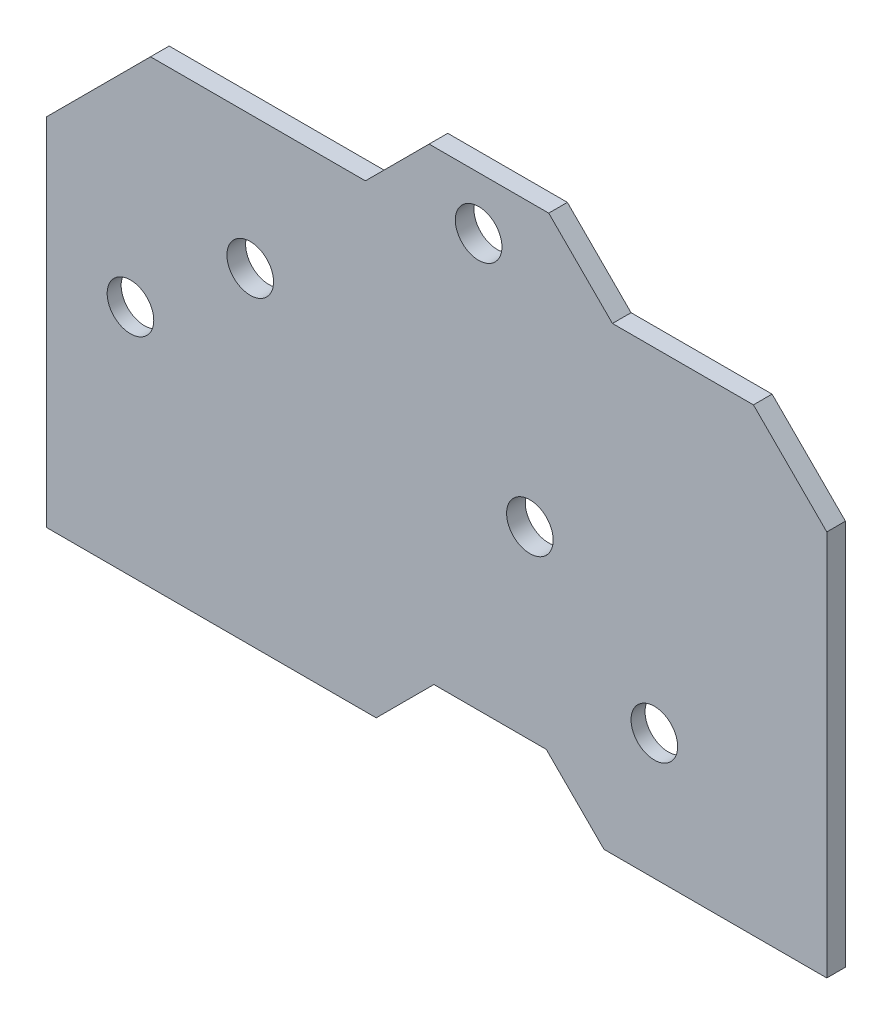
SolidWorks part; units mm, degrees
ref_plane "정면" through (0, 0, 0) normal (0, 0, 1) x (1, 0, 0)
ref_plane "윗면" through (0, 0, 0) normal (0, 1, 0) x (1, 0, 0)
ref_plane "우측면" through (0, 0, 0) normal (1, 0, 0) x (0, 0, -1)
sketch "스케치1" plane through (0, 0, 0) normal (0, 0, 1) x (1, 0, 0)
  line L0 (-7.6862, -28.1969) -> (-1.494, -22.0047)
  line L1 (-2.0116, 27.949) -> (10.8212, 27.949)
  line L2 (-43.0492, 9.9642) -> (-43.0492, -28.1969)
  line L3 (-43.0492, -28.1969) -> (-7.6862, -28.1969)
  line L4 (40.6497, 13.245) -> (40.6497, -28.1969)
  line L5 (-1.494, -22.0047) -> (10.5566, -22.0047)
  line L6 (10.5566, -22.0047) -> (16.7488, -28.1969)
  line L7 (16.7488, -28.1969) -> (40.6497, -28.1969)
  line L8 (-31.8983, 21.115) -> (-43.0492, 9.9642)
  line L9 (32.7797, 21.115) -> (40.6497, 13.245)
  line L10 (-2.0116, 27.949) -> (-8.8456, 21.115)
  line L11 (-8.8456, 21.115) -> (-31.8983, 21.115)
  line L12 (10.8212, 27.949) -> (17.6552, 21.115)
  line L13 (17.6552, 21.115) -> (32.7797, 21.115)
  circle A0 centre (-21.1998, 6.8031) radius 2.5
  circle A1 centre (3.3002, 22.3031) radius 2.5
  circle A2 centre (8.8002, -2.1969) radius 2.5
  circle A3 centre (-34.0492, -3.1969) radius 5.2
  circle A4 centre (-34.0492, -3.1969) radius 2.5
  circle A5 centre (22.1497, -14.6969) radius 5.2
  circle A6 centre (22.1497, -14.6969) radius 2.5
  point P0 (-1.1998, -0.6969)
  dimension "D1" = 5
  dimension "D2" = 5
  dimension "D3" = 5
  dimension "D9" = 5
  dimension "D10" = 10.4
  dimension "D11" = 5
  dimension "D12" = 10.4
  dimension "D13" = 9
  dimension "D4" = 24.5
  dimension "D5" = 24.5
  dimension "D6" = 30
  dimension "D7" = 15.5
  dimension "D8" = 9
  dimension "D14" = 25
  dimension "D15" = 18.5
  dimension "D16" = 13.5
extrude "보스-돌출1" add sketch "스케치1" along normal blind 2 contours L13 L12 L1 L10 L11 L8 L2 L3 L0 L5 L6 L7 L4 L9 A5 A3 A2 A1 A0
sketch "스케치3" plane through (0, 0, 2) normal (0, 0, 1) x (1, 0, 0)
  circle A0 centre (-34.0492, -3.1969) radius 5.2 construction
  circle A1 centre (-34.0492, -3.1969) radius 5.2
  circle A2 centre (-34.0492, -3.1969) radius 2.5
  circle A3 centre (22.1497, -14.6969) radius 5.2 construction
  circle A4 centre (22.1497, -14.6969) radius 5.2
  circle A5 centre (22.1497, -14.6969) radius 2.5
  dimension "D1" = 5
  dimension "D2" = 5
extrude "보스-돌출3" add sketch "스케치3" against normal blind 1.5
